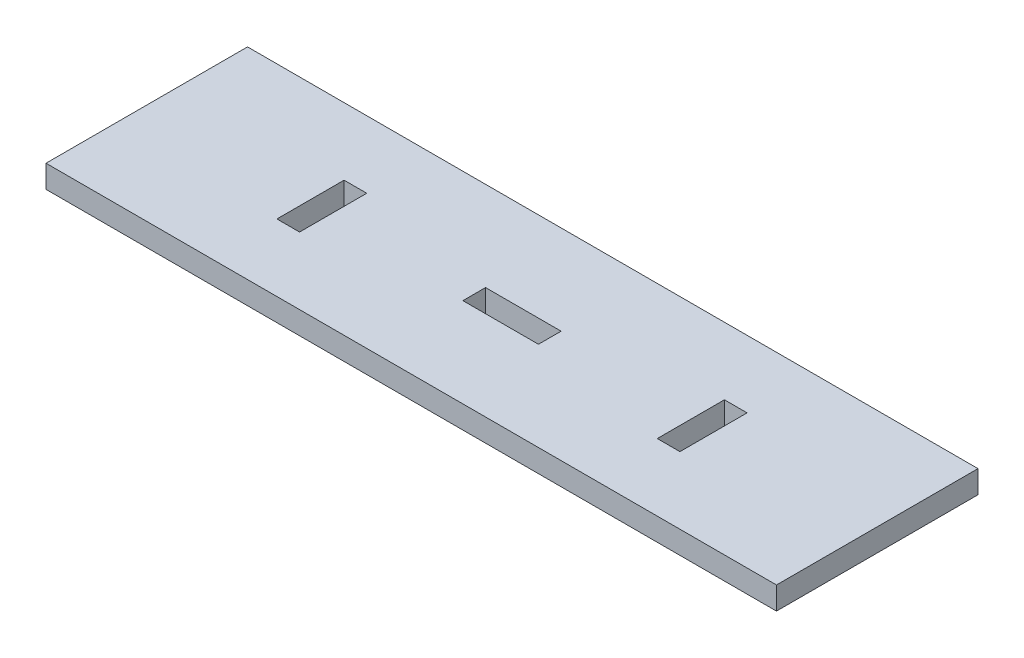
SolidWorks part; units mm, degrees
ref_plane "Front Plane" through (0, 0, 0) normal (0, 0, 1) x (1, 0, 0)
ref_plane "Top Plane" through (0, 0, 0) normal (0, 1, 0) x (1, 0, 0)
ref_plane "Right Plane" through (0, 0, 0) normal (1, 0, 0) x (0, 0, -1)
sketch "Sketch1" plane through (0, 0, 0) normal (0, 1, 0) x (1, 0, 0)
  line L0 (145, 80) -> (145, 0) construction
  line L1 (0, 0) -> (290, 0)
  line L2 (0, 0) -> (0, 80)
  line L3 (0, 80) -> (290, 80)
  line L4 (290, 0) -> (290, 80)
  line L5 (65, 53.3333) -> (74, 53.3333)
  line L6 (65, 80) -> (74, 80)
  line L7 (65, 80) -> (65, 0)
  line L8 (65, 0) -> (74, 0)
  line L9 (74, 80) -> (74, 0)
  line L10 (74, 26.6667) -> (65, 26.6667)
  line L11 (6.8547, 80) -> (6.8547, 53.3333) construction
  line L12 (6.8547, 53.3333) -> (6.8547, 26.6667) construction
  line L13 (6.8547, 26.6667) -> (6.8547, 0) construction
  line L14 (216, 26.6667) -> (225, 26.6667)
  line L15 (216, 80) -> (216, 0)
  line L16 (225, 0) -> (216, 0)
  line L17 (225, 80) -> (225, 0)
  line L18 (225, 80) -> (216, 80)
  line L19 (225, 53.3333) -> (216, 53.3333)
  line L20 (0, 40) -> (290, 40) construction
  line L21 (130, 44.5) -> (160, 44.5)
  line L22 (130, 44.5) -> (130, 35.5)
  line L23 (130, 35.5) -> (160, 35.5)
  line L24 (160, 44.5) -> (160, 35.5)
  point P33 (130, 40)
  point P34 (145, 44.5)
  dimension "D1" = 290
  dimension "D2" = 80
  dimension "D3" = 9
  dimension "D4" = 80
  dimension "9" = 9
  dimension "D5" = 30
extrude "Boss-Extrude1" add sketch "Sketch1" along normal blind 9 contours L15 L3 L9 L1 L21 L24 L23 L22 | L9 L3 L7 L5 | L9 L10 L7 L1 | L7 L3 L2 L1 | L3 L17 L1 L4 | L17 L14 L15 L1 | L19 L17 L3 L15
equation "\"D4@Sketch1\"=160/2"
